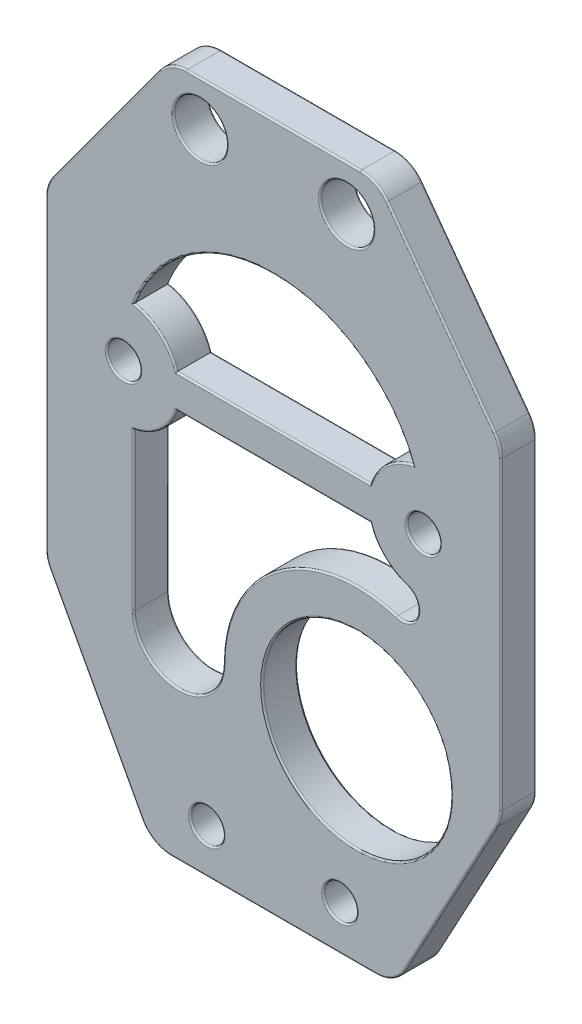
SolidWorks part; units mm, degrees
ref_plane "Front Plane" through (0, 0, 0) normal (0, 0, 1) x (1, 0, 0)
ref_plane "Top Plane" through (0, 0, 0) normal (0, 1, 0) x (1, 0, 0)
ref_plane "Right Plane" through (0, 0, 0) normal (1, 0, 0) x (0, 0, -1)
sketch "Sketch2" plane through (0, 0, 0) normal (0, 0, 1) x (1, 0, 0)
  line L0 (-11, 0) -> (11, 0)
  line L1 (11, 0) -> (20.5, 17.5997)
  line L7 (-20.5, 17.5997) -> (-11, 0)
  line L8 (20.5, 17.5997) -> (20.5, 46.7952)
  line L9 (20.5, 46.7952) -> (9.3584, 62)
  line L10 (9.3584, 62) -> (-9.3584, 62)
  line L11 (-9.3584, 62) -> (-20.5, 46.7952)
  line L12 (-20.5, 46.7952) -> (-20.5, 17.5997)
  line L13 (-12.5741, 31.5817) -> (-12.5741, 17.4164)
  line L14 (0, 62) -> (0, 0) construction
  line L15 (-8.7303, 37.9952) -> (8.7303, 37.9952)
  line L17 (-8.7303, 34.9952) -> (8.7303, 34.9952)
  line L19 (-8.7303, 37.9952) -> (8.7303, 34.9952) construction
  line L20 (-8.7303, 34.9952) -> (8.7303, 37.9952) construction
  line L21 (13.5, 36.4952) -> (11.1, 28.8637) construction
  circle A0 centre (7.5, 17.4164) radius 8.5
  arc A1 (19.337, 15.4451) -> (15.6435, 8.6026) centre (7.5, 17.4164) ccw
  circle A2 centre (13.5, 36.4952) radius 1.5
  circle A3 centre (13.5, 36.4952) radius 5
  circle A4 centre (-13.5, 36.4952) radius 1.5
  circle A5 centre (-13.5, 36.4952) radius 5
  arc A7 (11.1, 28.8637) -> (12, 31.7255) centre (11.55, 30.2946) ccw
  arc A8 (-12.5741, 17.4164) -> (-4.5, 17.4164) centre (-8.537, 17.4164) ccw
  circle A9 centre (-6.6084, 58) radius 2.395
  circle A10 centre (6.6084, 58) radius 2.395
  circle A11 centre (-6, 4) radius 1.5
  circle A12 centre (6, 4) radius 1.5
  arc A13 (12.5741, 41.4087) -> (-12.5741, 41.4087) centre (0, 36.4952) ccw
  point P19 (13.5, 36.2574)
  point P21 (0, 0)
  point P22 (11.2938, 28.8009)
  point P25 (0, 0)
  point P40 (11, 28.8009)
  point P41 (12.0282, 31.2527)
  point P42 (11.589, 28.6982)
  point P43 (0, 0)
  point P44 (0, 0)
  point P45 (0, 0)
  point P47 (-13.5, 37.1817)
  point P48 (-12.5741, 31.7255)
  point P49 (0, 0)
  point P53 (4.269, 55.9703)
  point P55 (8.7303, 61.4587)
  dimension "D4" = 3.5
  dimension "D5" = 17
  dimension "D7" = 3
  dimension "D9" = 3.5
  dimension "D10" = 3
  dimension "D12" = 13.5
  dimension "D14" = 7
  dimension "D15" = 1.5
  dimension "D16" = 4.79
  dimension "D1" = 20.5
  dimension "D2" = 20
  dimension "D3" = 11
  dimension "D6" = 4
  dimension "6" = 6
  dimension "D8" = 13
  dimension "D11" = 3
  dimension "D13" = 10.3
  dimension "D17" = 18.85
  dimension "D18" = 2.75
  dimension "D19" = 4
  dimension "D20" = 62
extrude "Boss-Extrude1" add sketch "Sketch2" along normal blind 3.175 contours A13 A3 A7 A1 L1 L8 L9 L10 L11 L12 L7 L0 A12 A8 L13 A5 A11 A10 A9 | A5 A4 | A5 L17 A3 L15 | A3 A2 | L1 A1 A0
fillet "Fillet1" radius 3 8 edges at (9.3584, 62, 1.5875) (20.5, 46.7952, 1.5875) (20.5, 17.5997, 1.5875) (11, 0, 1.5875) (-11, 0, 1.5875) (-20.5, 17.5997, 1.5875) (-20.5, 46.7952, 1.5875) (-9.3584, 62, 1.5875)
fillet "Fillet2" radius 0.15 68 edges at (15, 36.4952, 3.175) (15, 36.4952, 0) (16, 17.4164, 3.175) (16, 17.4164, 0) (-12, 36.4952, 3.175) (-12, 36.4952, 0) (-4.2134, 58, 3.175) (-4.2134, 58, 0) (9.0034, 58, 3.175) (9.0034, 58, 0) (-4.5, 4, 3.175) (-4.5, 4, 0) (7.5, 4, 3.175) (7.5, 4, 0) (-9.194, 61.6758, 3.175) (-9.194, 61.6758, 0) (-15.0886, 54.1801, 0) (-15.0886, 54.1801, 3.175) (-20.3513, 46.7465, 3.175) (-20.3513, 46.7465, 0) (-20.5, 32.0857, 0) (-20.5, 32.0857, 3.175) (-20.4086, 17.6228, 3.175) (-20.4086, 17.6228, 0) (-15.9951, 9.2539, 0) (-15.9951, 9.2539, 3.175) (-10.7472, 0.4237, 3.175) (-10.7472, 0.4237, 0) (0, 0, 0) (0, 0, 3.175) (10.7472, 0.4237, 3.175) (10.7472, 0.4237, 0) (15.9951, 9.2539, 0) (15.9951, 9.2539, 3.175) (20.4086, 17.6228, 3.175) (20.4086, 17.6228, 0) (20.5, 32.0857, 0) (20.5, 32.0857, 3.175) (20.3513, 46.7465, 3.175) (20.3513, 46.7465, 0) (15.0886, 54.1801, 0) (15.0886, 54.1801, 3.175) (9.194, 61.6758, 3.175) (9.194, 61.6758, 0) (0, 62, 3.175) (0, 62, 0) (0, 37.9952, 0) (0, 37.9952, 3.175) (-10.1799, 40.2338, 0) (-10.1799, 40.2338, 3.175) (0, 49.9952, 0) (0, 49.9952, 3.175) (10.1799, 40.2338, 0) (10.1799, 40.2338, 3.175) (9.9645, 32.9597, 0) (9.9645, 32.9597, 3.175) (12.9809, 29.8446, 0) (12.9809, 29.8446, 3.175) (0.4007, 27.0911, 0) (0.4007, 27.0911, 3.175) (-8.537, 13.3794, 0) (-8.537, 13.3794, 3.175) (-12.5741, 24.499, 0) (-12.5741, 24.499, 3.175) (-10.1799, 32.7566, 0) (-10.1799, 32.7566, 3.175) (0, 34.9952, 0) (0, 34.9952, 3.175)
